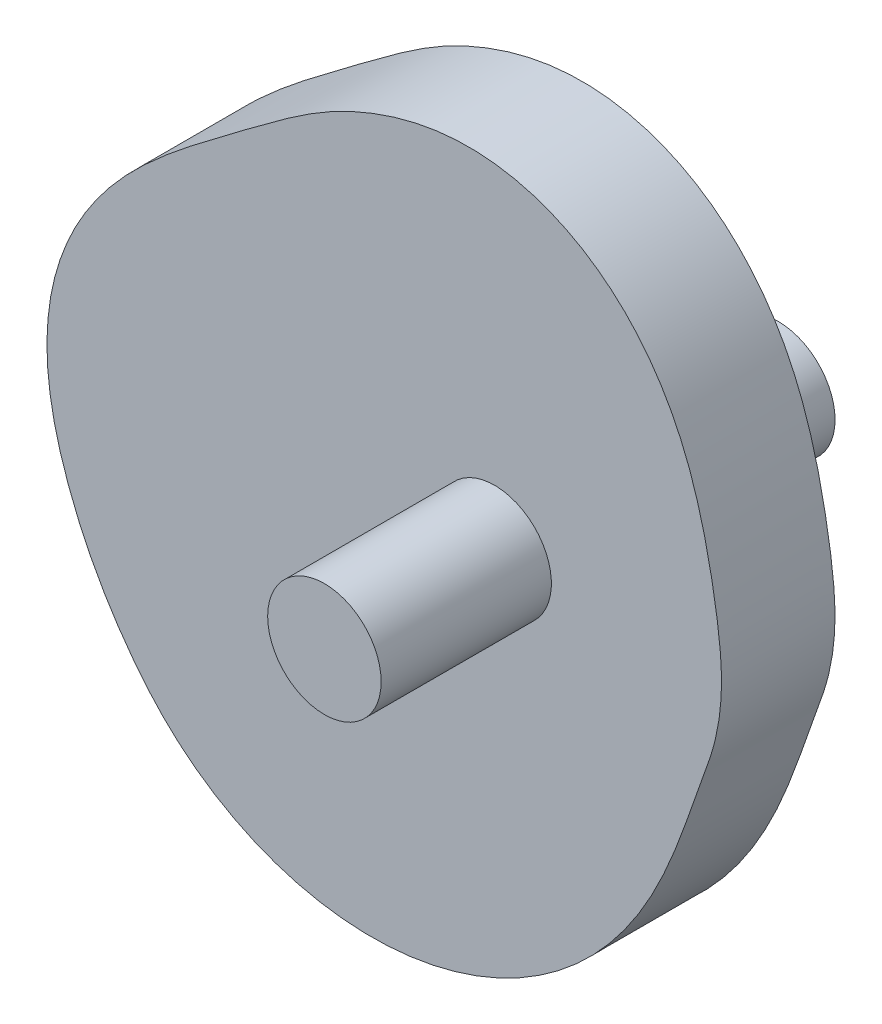
SolidWorks part; units mm, degrees
ref_plane "Front Plane" through (0, 0, 0) normal (0, 0, 1) x (1, 0, 0)
ref_plane "Top Plane" through (0, 0, 0) normal (0, 1, 0) x (1, 0, 0)
ref_plane "Right Plane" through (0, 0, 0) normal (1, 0, 0) x (0, 0, -1)
sketch "Sketch5" plane through (0, 0, 0) normal (0, 0, 1) x (1, 0, 0)
  circle A0 centre (0, 0) radius 5
  dimension "D1" = 10
extrude "Boss-Extrude3" add sketch "Sketch5" along normal mid plane 40
curve "Curve2"
  spline degree 3 poles (20.0011, -0.3491, 0) (20.0008, 0.3491, 0) (19.9777, 1.047, 0) (19.9354, 1.7442, 0) (19.8764, 2.4408, 0) (19.8034, 3.137, 0) (19.7182, 3.8335, 0) (19.6224, 4.5312, 0) (19.5172, 5.231, 0) (19.4033, 5.9339, 0) (19.2809, 6.6411, 0) (19.1501, 7.3536, 0) (19.0104, 8.0723, 0) (18.8611, 8.7983, 0) (18.7011, 9.5322, 0) (18.529, 10.2745, 0) (18.3433, 11.0257, 0) (18.1423, 11.7858, 0) (17.924, 12.5546, 0) (17.6864, 13.3318, 0) (17.4274, 14.1165, 0) (17.1449, 14.9078, 0) (16.8367, 15.7044, 0) (16.5009, 16.5046, 0) (16.1354, 17.3065, 0) (15.7384, 18.1081, 0) (15.3082, 18.9069, 0) (14.8433, 19.7002, 0) (14.3425, 20.4853, 0) (13.8047, 21.2591, 0) (13.2292, 22.0183, 0) (12.6156, 22.7599, 0) (11.9636, 23.4803, 0) (11.2736, 24.1762, 0) (10.546, 24.8441, 0) (9.7816, 25.4808, 0) (8.9816, 26.0828, 0) (8.1475, 26.6472, 0) (7.2811, 27.1707, 0) (6.3844, 27.6507, 0) (5.4599, 28.0846, 0) (4.51, 28.4701, 0) (3.5375, 28.8051, 0) (2.5455, 29.088, 0) (1.537, 29.3177, 0) (0.5153, 29.493, 0) (-0.5165, 29.6137, 0) (-1.5552, 29.6795, 0) (-2.5974, 29.691, 0) (-3.6403, 29.6489, 0) (-4.6809, 29.5545, 0) (-5.7166, 29.4095, 0) (-6.7451, 29.2159, 0) (-7.7642, 28.9764, 0) (-8.7726, 28.6939, 0) (-9.7691, 28.3715, 0) (-10.7532, 28.0131, 0) (-11.7243, 27.6208, 0) (-12.6811, 27.1948, 0) (-13.6225, 26.7356, 0) (-14.5473, 26.244, 0) (-15.4541, 25.72, 0) (-16.3436, 25.1668, 0) (-17.2187, 24.5904, 0) (-18.0827, 23.9955, 0) (-18.9392, 23.3862, 0) (-19.7921, 22.7655, 0) (-20.6453, 22.1356, 0) (-21.5023, 21.4975, 0) (-22.3666, 20.8513, 0) (-23.2407, 20.196, 0) (-24.1266, 19.5298, 0) (-25.0253, 18.8499, 0) (-25.9368, 18.153, 0) (-26.8601, 17.4352, 0) (-27.793, 16.6923, 0) (-28.7323, 15.9199, 0) (-29.6737, 15.1138, 0) (-30.6117, 14.2698, 0) (-31.5401, 13.3845, 0) (-32.452, 12.4548, 0) (-33.3397, 11.4786, 0) (-34.1952, 10.4544, 0) (-35.0105, 9.3818, 0) (-35.7774, 8.2614, 0) (-36.4881, 7.0947, 0) (-37.1353, 5.8842, 0) (-37.7123, 4.6332, 0) (-38.2134, 3.346, 0) (-38.6339, 2.0273, 0) (-38.9703, 0.6826, 0) (-39.2203, -0.6826, 0) (-39.3831, -2.0624, 0) (-39.459, -3.4511, 0) (-39.4496, -4.8431, 0) (-39.3578, -6.2332, 0) (-39.1876, -7.6171, 0) (-38.9438, -8.9908, 0) (-38.6319, -10.3514, 0) (-38.2581, -11.6967, 0) (-37.8287, -13.0255, 0) (-37.3507, -14.3376, 0) (-36.8277, -15.6324, 0) (-36.2597, -16.9082, 0) (-35.6475, -18.1633, 0) (-34.9919, -19.3963, 0) (-34.2937, -20.6057, 0) (-33.5536, -21.79, 0) (-32.7727, -22.9477, 0) (-31.952, -24.0776, 0) (-31.0919, -25.1776, 0) (-30.1957, -26.2487, 0) (-29.2407, -27.2676, 0) (-28.2326, -28.2329, 0) (-27.1741, -29.1412, 0) (-26.069, -29.9897, 0) (-24.9211, -30.7759, 0) (-23.7344, -31.4977, 0) (-22.513, -32.1531, 0) (-21.2611, -32.7406, 0) (-19.983, -33.2589, 0) (-18.6831, -33.707, 0) (-17.3658, -34.0844, 0) (-16.0356, -34.3907, 0) (-14.6969, -34.626, 0) (-13.3539, -34.7907, 0) (-12.0111, -34.8854, 0) (-10.6725, -34.9112, 0) (-9.3424, -34.8692, 0) (-8.0245, -34.7612, 0) (-6.7228, -34.5889, 0) (-5.4407, -34.3545, 0) (-4.1817, -34.0603, 0) (-2.9489, -33.7089, 0) (-1.7453, -33.3031, 0) (-0.5734, -32.8457, 0) (0.5642, -32.34, 0) (1.6655, -31.789, 0) (2.7287, -31.1963, 0) (3.752, -30.5651, 0) (4.7344, -29.8991, 0) (5.6749, -29.2016, 0) (6.5726, -28.4762, 0) (7.4274, -27.7265, 0) (8.239, -26.9557, 0) (9.0077, -26.1675, 0) (9.7339, -25.365, 0) (10.4183, -24.5513, 0) (11.0619, -23.7297, 0) (11.6658, -22.9029, 0) (12.2315, -22.0737, 0) (12.7605, -21.2446, 0) (13.2547, -20.4179, 0) (13.7159, -19.5958, 0) (14.1461, -18.78, 0) (14.5477, -17.9723, 0) (14.9228, -17.174, 0) (15.2738, -16.3862, 0) (15.603, -15.6099, 0) (15.9129, -14.8456, 0) (16.2057, -14.0938, 0) (16.484, -13.3544, 0) (16.7499, -12.6275, 0) (17.0057, -11.9126, 0) (17.2535, -11.2091, 0) (17.4953, -10.5162, 0) (17.733, -9.8329, 0) (17.9683, -9.1579, 0) (18.2028, -8.49, 0) (18.4378, -7.8275, 0) (18.6738, -7.1686, 0) (18.9146, -6.5129, 0) (19.1299, -5.8486, 0) (19.3225, -5.1774, 0) (19.4914, -4.4999, 0) (19.6365, -3.817, 0) (19.7578, -3.1293, 0) (19.855, -2.4379, 0) (19.9279, -1.7435, 0) (19.9766, -1.0469, 0) (20.0011, -0.3491, 0) (20.0008, 0.3491, 0) (19.9777, 1.047, 0) knots -0.010869 -0.007246 -0.003623 0 0.003623 0.007248 0.010874 0.014506 0.018147 0.0218 0.02547 0.029164 0.032887 0.036644 0.040442 0.044287 0.048184 0.052137 0.056152 0.060231 0.064378 0.068595 0.072883 0.077243 0.081675 0.086179 0.090753 0.095395 0.100104 0.104876 0.109709 0.114599 0.119543 0.124538 0.12958 0.134666 0.139791 0.144953 0.150149 0.155374 0.160626 0.165903 0.171202 0.176521 0.181857 0.187209 0.192575 0.197953 0.203342 0.208741 0.214149 0.219564 0.224985 0.230411 0.235841 0.241273 0.246707 0.252141 0.257576 0.26301 0.268445 0.27388 0.279314 0.284749 0.290184 0.295621 0.301063 0.306515 0.311986 0.317486 0.323027 0.328623 0.334288 0.340037 0.345881 0.351833 0.357901 0.36409 0.370402 0.376835 0.383385 0.390045 0.396806 0.403656 0.410584 0.417577 0.424625 0.431714 0.438837 0.445985 0.453151 0.460331 0.467521 0.474719 0.481925 0.489138 0.496359 0.503585 0.510819 0.518057 0.525299 0.532544 0.53979 0.547036 0.554282 0.561528 0.568774 0.57602 0.583267 0.590513 0.597759 0.605005 0.612251 0.619497 0.626742 0.633983 0.641219 0.648447 0.655665 0.662871 0.670062 0.677237 0.684392 0.691526 0.698635 0.705717 0.712769 0.719789 0.726774 0.73372 0.740625 0.747485 0.754299 0.761061 0.76777 0.774421 0.781013 0.78754 0.794 0.80039 0.806706 0.812946 0.819105 0.825181 0.83117 0.83707 0.842879 0.848592 0.854209 0.859726 0.865143 0.870456 0.875665 0.880769 0.885767 0.890659 0.895444 0.900125 0.904702 0.909177 0.913552 0.91783 0.922017 0.926115 0.93013 0.934068 0.937937 0.941743 0.945495 0.949201 0.952872 0.956517 0.960146 0.963769 0.967392 0.971015 0.974638 0.978261 0.981885 0.985508 0.989131 0.992754 0.996377 1 1.003623 1.007248 1.010874 periodic
sketch "Sketch9" plane through (0, 0, 0) normal (0, 0, 1) x (1, 0, 0)
  spline S0 degree 3 poles (20.0011, -0.3491) (20.0008, 0.3491) (19.9777, 1.047) (19.9354, 1.7442) (19.8764, 2.4408) (19.8034, 3.137) (19.7182, 3.8335) (19.6224, 4.5312) (19.5172, 5.231) (19.4033, 5.9339) (19.2809, 6.6411) (19.1501, 7.3536) (19.0104, 8.0723) (18.8611, 8.7983) (18.7011, 9.5322) (18.529, 10.2745) (18.3433, 11.0257) (18.1423, 11.7858) (17.924, 12.5546) (17.6864, 13.3318) (17.4274, 14.1165) (17.1449, 14.9078) (16.8367, 15.7044) (16.5009, 16.5046) (16.1354, 17.3065) (15.7384, 18.1081) (15.3082, 18.9069) (14.8433, 19.7002) (14.3425, 20.4853) (13.8047, 21.2591) (13.2292, 22.0183) (12.6156, 22.7599) (11.9636, 23.4803) (11.2736, 24.1762) (10.546, 24.8441) (9.7816, 25.4808) (8.9816, 26.0828) (8.1475, 26.6472) (7.2811, 27.1707) (6.3844, 27.6507) (5.4599, 28.0846) (4.51, 28.4701) (3.5375, 28.8051) (2.5455, 29.088) (1.537, 29.3177) (0.5153, 29.493) (-0.5165, 29.6137) (-1.5552, 29.6795) (-2.5974, 29.691) (-3.6403, 29.6489) (-4.6809, 29.5545) (-5.7166, 29.4095) (-6.7451, 29.2159) (-7.7642, 28.9764) (-8.7726, 28.6939) (-9.7691, 28.3715) (-10.7532, 28.0131) (-11.7243, 27.6208) (-12.6811, 27.1948) (-13.6225, 26.7356) (-14.5473, 26.244) (-15.4541, 25.72) (-16.3436, 25.1668) (-17.2187, 24.5904) (-18.0827, 23.9955) (-18.9392, 23.3862) (-19.7921, 22.7655) (-20.6453, 22.1356) (-21.5023, 21.4975) (-22.3666, 20.8513) (-23.2407, 20.196) (-24.1266, 19.5298) (-25.0253, 18.8499) (-25.9368, 18.153) (-26.8601, 17.4352) (-27.793, 16.6923) (-28.7323, 15.9199) (-29.6737, 15.1138) (-30.6117, 14.2698) (-31.5401, 13.3845) (-32.452, 12.4548) (-33.3397, 11.4786) (-34.1952, 10.4544) (-35.0105, 9.3818) (-35.7774, 8.2614) (-36.4881, 7.0947) (-37.1353, 5.8842) (-37.7123, 4.6332) (-38.2134, 3.346) (-38.6339, 2.0273) (-38.9703, 0.6826) (-39.2203, -0.6826) (-39.3831, -2.0624) (-39.459, -3.4511) (-39.4496, -4.8431) (-39.3578, -6.2332) (-39.1876, -7.6171) (-38.9438, -8.9908) (-38.6319, -10.3514) (-38.2581, -11.6967) (-37.8287, -13.0255) (-37.3507, -14.3376) (-36.8277, -15.6324) (-36.2597, -16.9082) (-35.6475, -18.1633) (-34.9919, -19.3963) (-34.2937, -20.6057) (-33.5536, -21.79) (-32.7727, -22.9477) (-31.952, -24.0776) (-31.0919, -25.1776) (-30.1957, -26.2487) (-29.2407, -27.2676) (-28.2326, -28.2329) (-27.1741, -29.1412) (-26.069, -29.9897) (-24.9211, -30.7759) (-23.7344, -31.4977) (-22.513, -32.1531) (-21.2611, -32.7406) (-19.983, -33.2589) (-18.6831, -33.707) (-17.3658, -34.0844) (-16.0356, -34.3907) (-14.6969, -34.626) (-13.3539, -34.7907) (-12.0111, -34.8854) (-10.6725, -34.9112) (-9.3424, -34.8692) (-8.0245, -34.7612) (-6.7228, -34.5889) (-5.4407, -34.3545) (-4.1817, -34.0603) (-2.9489, -33.7089) (-1.7453, -33.3031) (-0.5734, -32.8457) (0.5642, -32.34) (1.6655, -31.789) (2.7287, -31.1963) (3.752, -30.5651) (4.7344, -29.8991) (5.6749, -29.2016) (6.5726, -28.4762) (7.4274, -27.7265) (8.239, -26.9557) (9.0077, -26.1675) (9.7339, -25.365) (10.4183, -24.5513) (11.0619, -23.7297) (11.6658, -22.9029) (12.2315, -22.0737) (12.7605, -21.2446) (13.2547, -20.4179) (13.7159, -19.5958) (14.1461, -18.78) (14.5477, -17.9723) (14.9228, -17.174) (15.2738, -16.3862) (15.603, -15.6099) (15.9129, -14.8456) (16.2057, -14.0938) (16.484, -13.3544) (16.7499, -12.6275) (17.0057, -11.9126) (17.2535, -11.2091) (17.4953, -10.5162) (17.733, -9.8329) (17.9683, -9.1579) (18.2028, -8.49) (18.4378, -7.8275) (18.6738, -7.1686) (18.9146, -6.5129) (19.1299, -5.8486) (19.3225, -5.1774) (19.4914, -4.4999) (19.6365, -3.817) (19.7578, -3.1293) (19.855, -2.4379) (19.9279, -1.7435) (19.9766, -1.0469) (20.0011, -0.3491) (20.0008, 0.3491) (19.9777, 1.047) knots -0.010869 -0.007246 -0.003623 0 0.003623 0.007248 0.010874 0.014506 0.018147 0.0218 0.02547 0.029164 0.032887 0.036644 0.040442 0.044287 0.048184 0.052137 0.056152 0.060231 0.064378 0.068595 0.072883 0.077243 0.081675 0.086179 0.090753 0.095395 0.100104 0.104876 0.109709 0.114599 0.119543 0.124538 0.12958 0.134666 0.139791 0.144953 0.150149 0.155374 0.160626 0.165903 0.171202 0.176521 0.181857 0.187209 0.192575 0.197953 0.203342 0.208741 0.214149 0.219564 0.224985 0.230411 0.235841 0.241273 0.246707 0.252141 0.257576 0.26301 0.268445 0.27388 0.279314 0.284749 0.290184 0.295621 0.301063 0.306515 0.311986 0.317486 0.323027 0.328623 0.334288 0.340037 0.345881 0.351833 0.357901 0.36409 0.370402 0.376835 0.383385 0.390045 0.396806 0.403656 0.410584 0.417577 0.424625 0.431714 0.438837 0.445985 0.453151 0.460331 0.467521 0.474719 0.481925 0.489138 0.496359 0.503585 0.510819 0.518057 0.525299 0.532544 0.53979 0.547036 0.554282 0.561528 0.568774 0.57602 0.583267 0.590513 0.597759 0.605005 0.612251 0.619497 0.626742 0.633983 0.641219 0.648447 0.655665 0.662871 0.670062 0.677237 0.684392 0.691526 0.698635 0.705717 0.712769 0.719789 0.726774 0.73372 0.740625 0.747485 0.754299 0.761061 0.76777 0.774421 0.781013 0.78754 0.794 0.80039 0.806706 0.812946 0.819105 0.825181 0.83117 0.83707 0.842879 0.848592 0.854209 0.859726 0.865143 0.870456 0.875665 0.880769 0.885767 0.890659 0.895444 0.900125 0.904702 0.909177 0.913552 0.91783 0.922017 0.926115 0.93013 0.934068 0.937937 0.941743 0.945495 0.949201 0.952872 0.956517 0.960146 0.963769 0.967392 0.971015 0.974638 0.978261 0.981885 0.985508 0.989131 0.992754 0.996377 1 1.003623 1.007248 1.010874 only from (19.997, 0.349) to (19.997, 0.349) construction
  spline S1 degree 3 poles (20.0011, -0.3491) (20.0008, 0.3491) (19.9777, 1.047) (19.9354, 1.7442) (19.8764, 2.4408) (19.8034, 3.137) (19.7182, 3.8335) (19.6224, 4.5312) (19.5172, 5.231) (19.4033, 5.9339) (19.2809, 6.6411) (19.1501, 7.3536) (19.0104, 8.0723) (18.8611, 8.7983) (18.7011, 9.5322) (18.529, 10.2745) (18.3433, 11.0257) (18.1423, 11.7858) (17.924, 12.5546) (17.6864, 13.3318) (17.4274, 14.1165) (17.1449, 14.9078) (16.8367, 15.7044) (16.5009, 16.5046) (16.1354, 17.3065) (15.7384, 18.1081) (15.3082, 18.9069) (14.8433, 19.7002) (14.3425, 20.4853) (13.8047, 21.2591) (13.2292, 22.0183) (12.6156, 22.7599) (11.9636, 23.4803) (11.2736, 24.1762) (10.546, 24.8441) (9.7816, 25.4808) (8.9816, 26.0828) (8.1475, 26.6472) (7.2811, 27.1707) (6.3844, 27.6507) (5.4599, 28.0846) (4.51, 28.4701) (3.5375, 28.8051) (2.5455, 29.088) (1.537, 29.3177) (0.5153, 29.493) (-0.5165, 29.6137) (-1.5552, 29.6795) (-2.5974, 29.691) (-3.6403, 29.6489) (-4.6809, 29.5545) (-5.7166, 29.4095) (-6.7451, 29.2159) (-7.7642, 28.9764) (-8.7726, 28.6939) (-9.7691, 28.3715) (-10.7532, 28.0131) (-11.7243, 27.6208) (-12.6811, 27.1948) (-13.6225, 26.7356) (-14.5473, 26.244) (-15.4541, 25.72) (-16.3436, 25.1668) (-17.2187, 24.5904) (-18.0827, 23.9955) (-18.9392, 23.3862) (-19.7921, 22.7655) (-20.6453, 22.1356) (-21.5023, 21.4975) (-22.3666, 20.8513) (-23.2407, 20.196) (-24.1266, 19.5298) (-25.0253, 18.8499) (-25.9368, 18.153) (-26.8601, 17.4352) (-27.793, 16.6923) (-28.7323, 15.9199) (-29.6737, 15.1138) (-30.6117, 14.2698) (-31.5401, 13.3845) (-32.452, 12.4548) (-33.3397, 11.4786) (-34.1952, 10.4544) (-35.0105, 9.3818) (-35.7774, 8.2614) (-36.4881, 7.0947) (-37.1353, 5.8842) (-37.7123, 4.6332) (-38.2134, 3.346) (-38.6339, 2.0273) (-38.9703, 0.6826) (-39.2203, -0.6826) (-39.3831, -2.0624) (-39.459, -3.4511) (-39.4496, -4.8431) (-39.3578, -6.2332) (-39.1876, -7.6171) (-38.9438, -8.9908) (-38.6319, -10.3514) (-38.2581, -11.6967) (-37.8287, -13.0255) (-37.3507, -14.3376) (-36.8277, -15.6324) (-36.2597, -16.9082) (-35.6475, -18.1633) (-34.9919, -19.3963) (-34.2937, -20.6057) (-33.5536, -21.79) (-32.7727, -22.9477) (-31.952, -24.0776) (-31.0919, -25.1776) (-30.1957, -26.2487) (-29.2407, -27.2676) (-28.2326, -28.2329) (-27.1741, -29.1412) (-26.069, -29.9897) (-24.9211, -30.7759) (-23.7344, -31.4977) (-22.513, -32.1531) (-21.2611, -32.7406) (-19.983, -33.2589) (-18.6831, -33.707) (-17.3658, -34.0844) (-16.0356, -34.3907) (-14.6969, -34.626) (-13.3539, -34.7907) (-12.0111, -34.8854) (-10.6725, -34.9112) (-9.3424, -34.8692) (-8.0245, -34.7612) (-6.7228, -34.5889) (-5.4407, -34.3545) (-4.1817, -34.0603) (-2.9489, -33.7089) (-1.7453, -33.3031) (-0.5734, -32.8457) (0.5642, -32.34) (1.6655, -31.789) (2.7287, -31.1963) (3.752, -30.5651) (4.7344, -29.8991) (5.6749, -29.2016) (6.5726, -28.4762) (7.4274, -27.7265) (8.239, -26.9557) (9.0077, -26.1675) (9.7339, -25.365) (10.4183, -24.5513) (11.0619, -23.7297) (11.6658, -22.9029) (12.2315, -22.0737) (12.7605, -21.2446) (13.2547, -20.4179) (13.7159, -19.5958) (14.1461, -18.78) (14.5477, -17.9723) (14.9228, -17.174) (15.2738, -16.3862) (15.603, -15.6099) (15.9129, -14.8456) (16.2057, -14.0938) (16.484, -13.3544) (16.7499, -12.6275) (17.0057, -11.9126) (17.2535, -11.2091) (17.4953, -10.5162) (17.733, -9.8329) (17.9683, -9.1579) (18.2028, -8.49) (18.4378, -7.8275) (18.6738, -7.1686) (18.9146, -6.5129) (19.1299, -5.8486) (19.3225, -5.1774) (19.4914, -4.4999) (19.6365, -3.817) (19.7578, -3.1293) (19.855, -2.4379) (19.9279, -1.7435) (19.9766, -1.0469) (20.0011, -0.3491) (20.0008, 0.3491) (19.9777, 1.047) knots -0.010869 -0.007246 -0.003623 0 0.003623 0.007248 0.010874 0.014506 0.018147 0.0218 0.02547 0.029164 0.032887 0.036644 0.040442 0.044287 0.048184 0.052137 0.056152 0.060231 0.064378 0.068595 0.072883 0.077243 0.081675 0.086179 0.090753 0.095395 0.100104 0.104876 0.109709 0.114599 0.119543 0.124538 0.12958 0.134666 0.139791 0.144953 0.150149 0.155374 0.160626 0.165903 0.171202 0.176521 0.181857 0.187209 0.192575 0.197953 0.203342 0.208741 0.214149 0.219564 0.224985 0.230411 0.235841 0.241273 0.246707 0.252141 0.257576 0.26301 0.268445 0.27388 0.279314 0.284749 0.290184 0.295621 0.301063 0.306515 0.311986 0.317486 0.323027 0.328623 0.334288 0.340037 0.345881 0.351833 0.357901 0.36409 0.370402 0.376835 0.383385 0.390045 0.396806 0.403656 0.410584 0.417577 0.424625 0.431714 0.438837 0.445985 0.453151 0.460331 0.467521 0.474719 0.481925 0.489138 0.496359 0.503585 0.510819 0.518057 0.525299 0.532544 0.53979 0.547036 0.554282 0.561528 0.568774 0.57602 0.583267 0.590513 0.597759 0.605005 0.612251 0.619497 0.626742 0.633983 0.641219 0.648447 0.655665 0.662871 0.670062 0.677237 0.684392 0.691526 0.698635 0.705717 0.712769 0.719789 0.726774 0.73372 0.740625 0.747485 0.754299 0.761061 0.76777 0.774421 0.781013 0.78754 0.794 0.80039 0.806706 0.812946 0.819105 0.825181 0.83117 0.83707 0.842879 0.848592 0.854209 0.859726 0.865143 0.870456 0.875665 0.880769 0.885767 0.890659 0.895444 0.900125 0.904702 0.909177 0.913552 0.91783 0.922017 0.926115 0.93013 0.934068 0.937937 0.941743 0.945495 0.949201 0.952872 0.956517 0.960146 0.963769 0.967392 0.971015 0.974638 0.978261 0.981885 0.985508 0.989131 0.992754 0.996377 1 1.003623 1.007248 1.010874 only from (19.997, 0.349) to (19.997, 0.349)
extrude "Boss-Extrude4" add sketch "Sketch9" along normal mid plane 10
